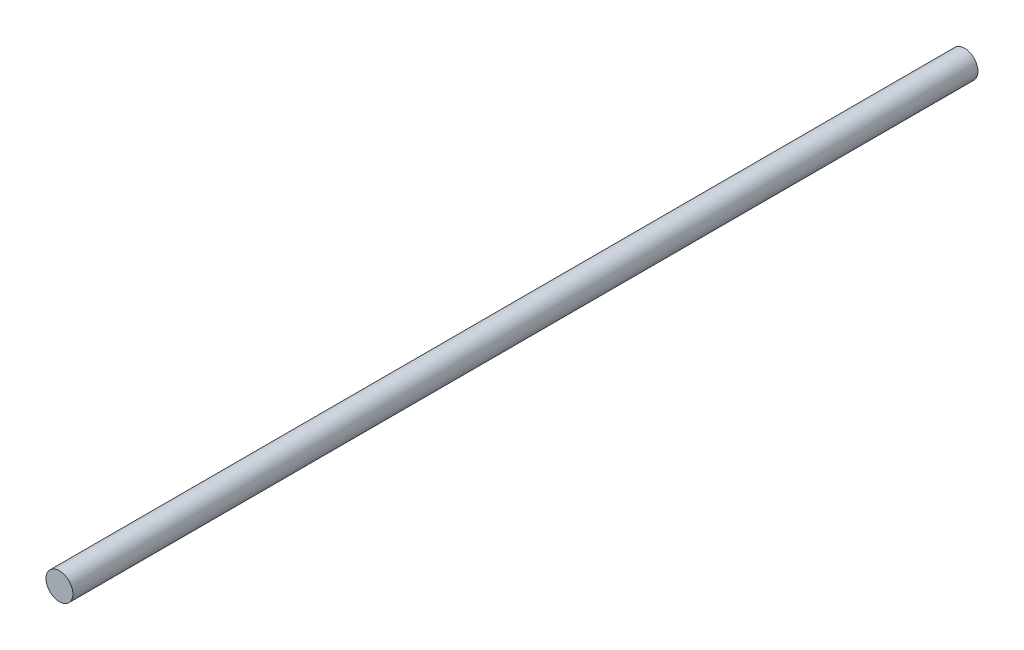
SolidWorks part; units mm, degrees
ref_plane "Front" through (0, 0, 0) normal (0, 0, 1) x (1, 0, 0)
ref_plane "Top" through (0, 0, 0) normal (0, 1, 0) x (1, 0, 0)
ref_plane "Right" through (0, 0, 0) normal (1, 0, 0) x (0, 0, -1)
sketch "Sketch1" plane through (0, 0, 0) normal (0, 0, 1) x (1, 0, 0)
  circle A0 centre (0, 0) radius 4.75
  dimension "D1" = 9.5
extrude "Boss-Extrude1" add sketch "Sketch1" along normal blind 320
equation "\"rod_length_zaxis\"=320"
equation "\"D1@Boss-Extrude1\"=\"rod_length_zaxis\""
